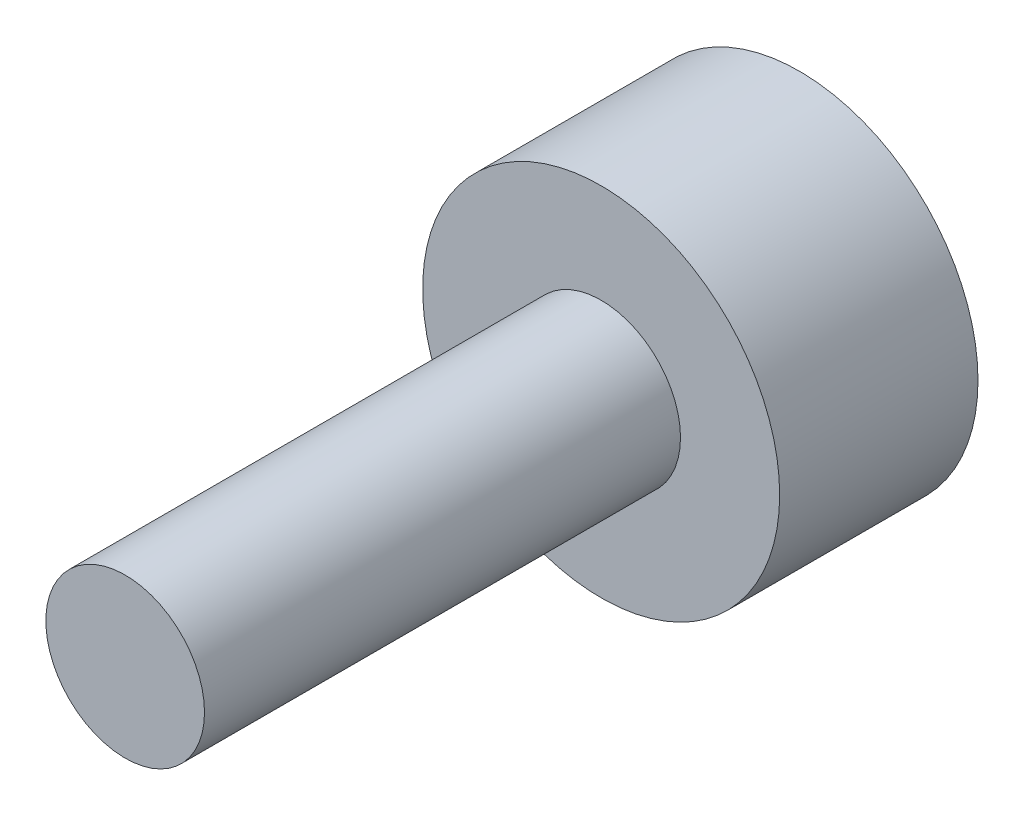
SolidWorks part; units mm, degrees
ref_plane "正面" through (0, 0, 0) normal (0, 0, 1) x (1, 0, 0)
ref_plane "平面" through (0, 0, 0) normal (0, 1, 0) x (1, 0, 0)
ref_plane "右側面" through (0, 0, 0) normal (1, 0, 0) x (0, 0, -1)
sketch "ｽｹｯﾁ1" plane through (0, 0, 0) normal (0, 0, 1) x (1, 0, 0)
  circle A0 centre (0, 0) radius 2.25
  dimension "D1" = 4.5
extrude "ﾎﾞｽ - 押し出し1" add sketch "ｽｹｯﾁ1" along normal blind 2.5
sketch "ｽｹｯﾁ2" plane through (0, 0, 2.5) normal (0, 0, 1) x (1, 0, 0)
  circle A0 centre (0, 0) radius 1
  dimension "D1" = 2
extrude "ﾎﾞｽ - 押し出し2" add sketch "ｽｹｯﾁ2" along normal blind 6
cosmetic thread "ねじ山1" parameters "D2"=1
sketch "ｽｹｯﾁ3" plane through (0, 0, 0) normal (0, 0, -1) x (-1, 0, 0)
  line L1 (0.8522, -0.7637) -> (1.0875, 0.3562)
  line L2 (1.0875, 0.3562) -> (0.2352, 1.1199)
  line L3 (0.2352, 1.1199) -> (-0.8522, 0.7637)
  line L4 (-0.8522, 0.7637) -> (-1.0875, -0.3562)
  line L5 (-1.0875, -0.3562) -> (-0.2352, -1.1199)
  line L6 (-0.2352, -1.1199) -> (0.8522, -0.7637)
  circle A0 centre (0, 0) radius 0.991 construction
extrude "ｶｯﾄ - 押し出し1" cut sketch "ｽｹｯﾁ3" against normal blind 2
